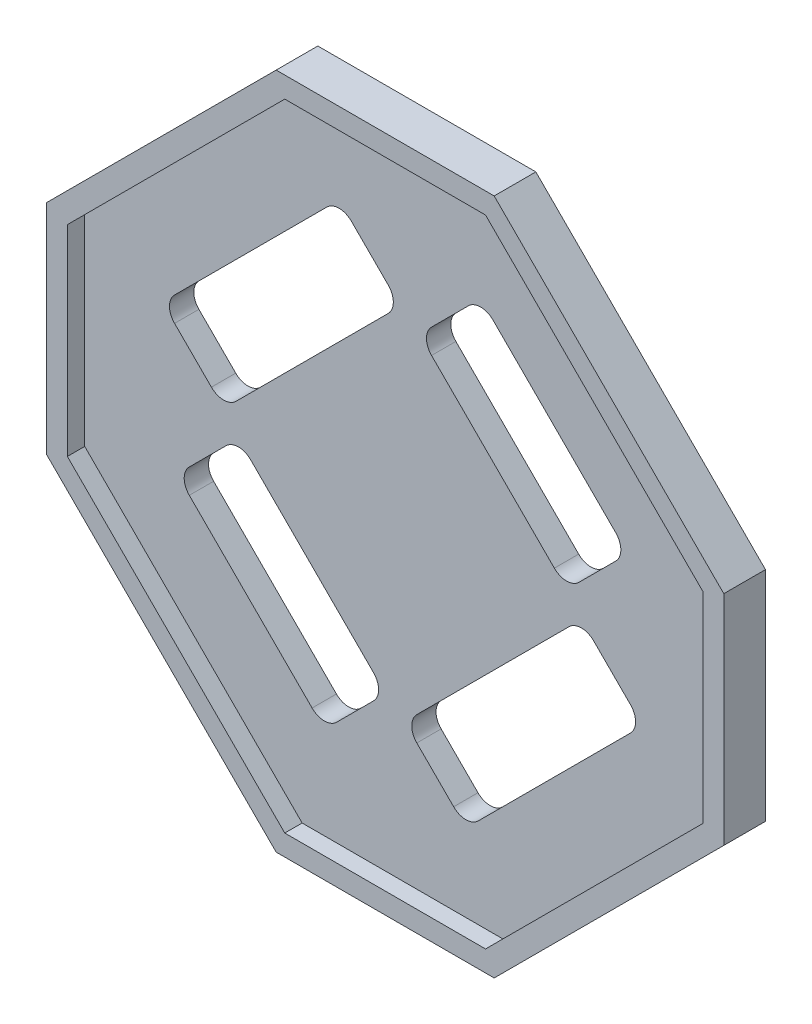
SolidWorks part; units mm, degrees
ref_plane "Plan de face" through (0, 0, 0) normal (0, 0, 1) x (1, 0, 0)
ref_plane "Plan de dessus" through (0, 0, 0) normal (0, 1, 0) x (1, 0, 0)
ref_plane "Plan de droite" through (0, 0, 0) normal (1, 0, 0) x (0, 0, -1)
sketch "Esquisse1" plane through (0, 0, 0) normal (0, 0, 1) x (1, 0, 0)
  line L5 (-45.75, 14.4507) -> (-14.4507, 45.75)
  line L6 (-14.4507, 45.75) -> (14.4507, 45.75)
  line L14 (14.4507, 45.75) -> (45.75, 14.4507)
  line L15 (45.75, 14.4507) -> (45.75, -14.4507)
  line L16 (45.75, -14.4507) -> (14.4507, -45.75)
  line L17 (-14.4507, -45.75) -> (14.4507, -45.75)
  line L18 (-14.4507, -45.75) -> (-45.75, -14.4507)
  line L19 (-45.75, -14.4507) -> (-45.75, 14.4507)
  line L22 (-13.0178, 13.0178) -> (-2.0577, 23.978)
  line L23 (-2.0577, 27.5135) -> (-7.361, 32.8168)
  line L24 (-27.5135, 2.0577) -> (-32.8168, 7.361)
  line L25 (-32.8168, 10.8965) -> (-10.8965, 32.8168)
  line L26 (-23.978, 2.0577) -> (-13.0178, 13.0178)
  line L27 (-13.0178, -13.0178) -> (-21.8567, -4.179)
  line L28 (-25.3922, -4.179) -> (-30.6955, -9.4823)
  line L29 (-4.179, -25.3922) -> (-9.4823, -30.6955)
  line L30 (-30.6955, -13.0178) -> (-13.0178, -30.6955)
  line L31 (-4.179, -21.8567) -> (-13.0178, -13.0178)
  line L32 (27.5135, -2.0577) -> (32.8168, -7.361)
  line L33 (13.0178, -13.0178) -> (23.978, -2.0577)
  line L34 (2.0577, -23.978) -> (13.0178, -13.0178)
  line L35 (2.0577, -27.5135) -> (7.361, -32.8168)
  line L36 (10.8965, -32.8168) -> (32.8168, -10.8965)
  line L37 (4.179, 25.3922) -> (9.4823, 30.6955)
  line L38 (13.0178, 30.6955) -> (30.6955, 13.0178)
  line L39 (25.3922, 4.179) -> (30.6955, 9.4823)
  line L40 (21.8567, 4.179) -> (13.0178, 13.0178)
  line L41 (13.0178, 13.0178) -> (4.179, 21.8567)
  arc A0 (-13.0178, -30.6955) -> (-9.4823, -30.6955) centre (-11.2501, -28.9277) ccw
  arc A1 (-4.179, -25.3922) -> (-4.179, -21.8567) centre (-5.9468, -23.6244) ccw
  arc A2 (-30.6955, -9.4823) -> (-30.6955, -13.0178) centre (-28.9277, -11.2501) ccw
  arc A3 (-21.8567, -4.179) -> (-25.3922, -4.179) centre (-23.6244, -5.9468) ccw
  arc A4 (-32.8168, 7.361) -> (-32.8168, 10.8965) centre (-31.0491, 9.1287) cw
  arc A5 (-27.5135, 2.0577) -> (-23.978, 2.0577) centre (-25.7458, 3.8254) ccw
  arc A6 (-2.0577, 23.978) -> (-2.0577, 27.5135) centre (-3.8254, 25.7458) ccw
  arc A7 (-7.361, 32.8168) -> (-10.8965, 32.8168) centre (-9.1287, 31.0491) ccw
  arc A8 (23.978, -2.0577) -> (27.5135, -2.0577) centre (25.7458, -3.8254) cw
  arc A9 (2.0577, -27.5135) -> (2.0577, -23.978) centre (3.8254, -25.7458) cw
  arc A10 (7.361, -32.8168) -> (10.8965, -32.8168) centre (9.1287, -31.0491) ccw
  arc A11 (32.8168, -7.361) -> (32.8168, -10.8965) centre (31.0491, -9.1287) cw
  arc A12 (4.179, 21.8567) -> (4.179, 25.3922) centre (5.9468, 23.6244) cw
  arc A13 (9.4823, 30.6955) -> (13.0178, 30.6955) centre (11.2501, 28.9277) cw
  arc A14 (30.6955, 13.0178) -> (30.6955, 9.4823) centre (28.9277, 11.2501) cw
  arc A15 (25.3922, 4.179) -> (21.8567, 4.179) centre (23.6244, 5.9468) cw
  point P0 (0, 0)
  point P9 (0, 45)
  point P12 (45, 0)
  point P15 (-45, 0)
  point P18 (0, -45)
  point P35 (-11.2501, -32.4633)
  point P38 (-2.4112, -23.6244)
  point P41 (-32.4633, -11.2501)
  point P44 (-23.6244, -2.4112)
  point P47 (-34.5846, 9.1287)
  point P50 (-25.7458, 0.2899)
  point P53 (-0.2899, 25.7458)
  point P56 (-9.1287, 34.5846)
  dimension "D12" = 2.5
  dimension "D8" = 18
  dimension "D9" = 12.5
  dimension "D10" = 15
  dimension "D11" = 12.5
extrude "Boss.-Extru.1" add sketch "Esquisse1" along normal blind 3.5
sketch "Esquisse2" plane through (0, 0, 0) normal (0, 0, 1) x (1, 0, 0)
  line L0 (-45.75, 14.4507) -> (-14.4507, 45.75)
  line L1 (-14.4507, 45.75) -> (14.4507, 45.75)
  line L2 (14.4507, 45.75) -> (45.75, 14.4507)
  line L3 (45.75, 14.4507) -> (45.75, -14.4507)
  line L4 (45.75, -14.4507) -> (14.4507, -45.75)
  line L5 (14.4507, -45.75) -> (-14.4507, -45.75)
  line L6 (-14.4507, -45.75) -> (-45.75, -14.4507)
  line L7 (-45.75, -14.4507) -> (-45.75, 14.4507)
  line L8 (-48.75, -15.6933) -> (-48.75, 15.6933)
  line L9 (-48.75, 15.6933) -> (-15.6933, 48.75)
  line L10 (-15.6933, 48.75) -> (15.6933, 48.75)
  line L11 (15.6933, 48.75) -> (48.75, 15.6933)
  line L12 (48.75, 15.6933) -> (48.75, -15.6933)
  line L13 (48.75, -15.6933) -> (15.6933, -48.75)
  line L14 (15.6933, -48.75) -> (-15.6933, -48.75)
  line L15 (-15.6933, -48.75) -> (-48.75, -15.6933)
  dimension "D1" = 3
extrude "Boss.-Extru.2" add sketch "Esquisse2" along normal blind 6
